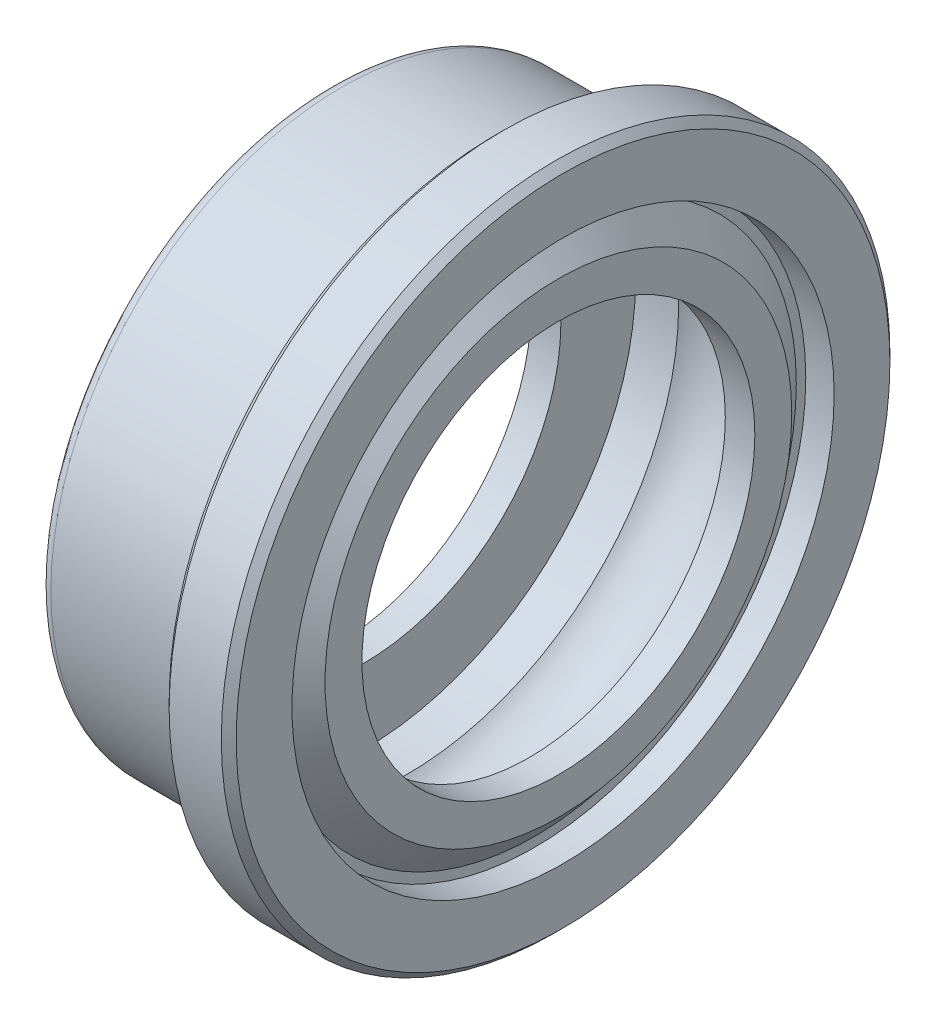
SolidWorks part; units mm, degrees
material "AISI 347 Annealed Stainless Steel (SS)"
ref_plane "Front Plane" through (0, 0, 0) normal (0, 0, 1) x (1, 0, 0)
ref_plane "Top Plane" through (0, 0, 0) normal (0, 1, 0) x (1, 0, 0)
ref_plane "Right Plane" through (0, 0, 0) normal (1, 0, 0) x (0, 0, -1)
sketch "Sketch1" plane through (0, 0, 0) normal (0, 0, 1) x (1, 0, 0)
  line L0 (0.5328, 3.6973) -> (1.1213, 3.6973)
  line L1 (1.1213, 3.6973) -> (1.1213, 2.6792)
  line L2 (1.1213, 2.6792) -> (1.524, 2.6792)
  line L3 (1.524, 2.6792) -> (1.524, 3.1826)
  line L4 (1.524, 3.1826) -> (1.2007, 3.5679)
  line L5 (1.2007, 3.5679) -> (1.2007, 3.6973)
  line L6 (1.2007, 3.6973) -> (1.5875, 3.6973)
  line L7 (1.5875, 3.6973) -> (1.5875, 4.4577)
  line L8 (1.5875, 4.4577) -> (1.4859, 4.5593)
  line L9 (1.4859, 4.5593) -> (0.7747, 4.5593)
  line L10 (0.7747, 4.5593) -> (0.6731, 4.4577)
  line L11 (0.6731, 4.4577) -> (0.6731, 4.1211)
  line L12 (0.5207, 3.9688) -> (-1.4287, 3.9688)
  line L13 (-1.5875, 3.81) -> (-1.5875, 3.6973)
  line L14 (-1.5875, 3.6973) -> (-1.2007, 3.6973)
  line L15 (-1.2007, 3.6973) -> (-1.2007, 3.5679)
  line L16 (-1.2007, 3.5679) -> (-1.524, 3.1826)
  line L17 (-1.524, 3.1826) -> (-1.524, 2.6792)
  line L18 (-1.524, 2.6792) -> (-1.1213, 2.6792)
  line L19 (-1.1213, 2.6792) -> (-1.1213, 3.6973)
  line L20 (-1.1213, 3.6973) -> (-0.5328, 3.6973)
  line L21 (-1.5875, 0) -> (1.5875, 0) construction
  arc A0 (0.6731, 4.1211) -> (0.5207, 3.9688) centre (0.5207, 4.1211) cw
  arc A1 (-1.4287, 3.9688) -> (-1.5875, 3.81) centre (-1.4287, 3.81) ccw
  arc A2 (-0.5328, 3.6973) -> (0.5328, 3.6973) centre (0, 3.175) cw
revolve "Revolve1" add sketch "Sketch1" angle 360 about L21
